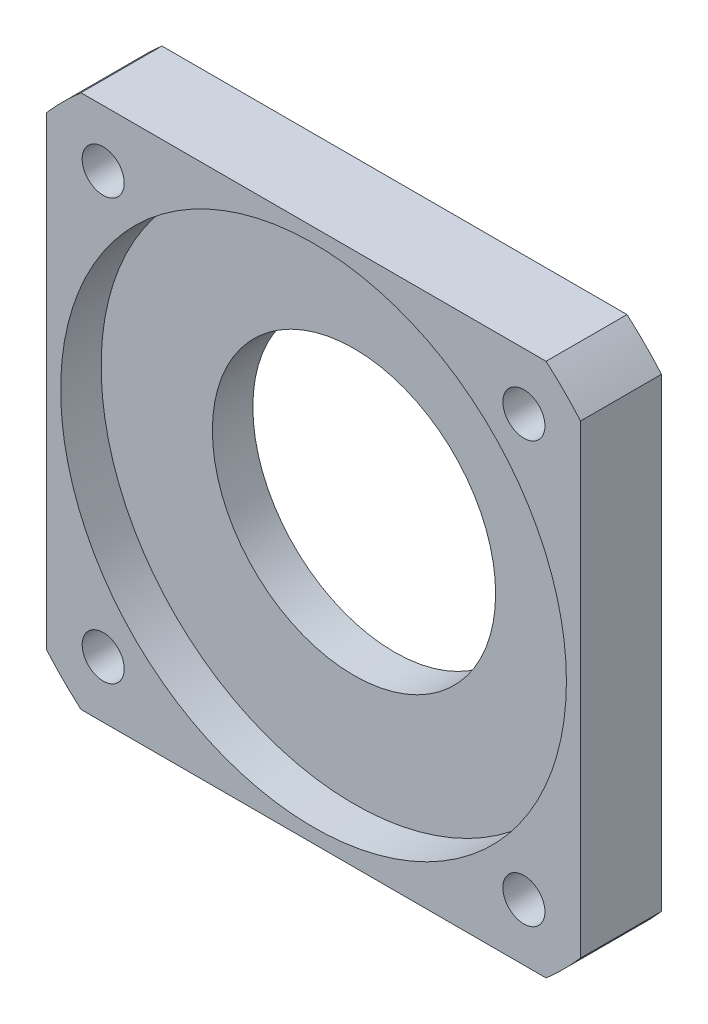
SolidWorks part; units mm, degrees
material "2024-T3"
ref_plane "Front Plane" through (0, 0, 0) normal (0, 0, 1) x (1, 0, 0)
ref_plane "Top Plane" through (0, 0, 0) normal (0, 1, 0) x (1, 0, 0)
ref_plane "Right Plane" through (0, 0, 0) normal (1, 0, 0) x (0, 0, -1)
sketch "Sketch1" plane through (0, 0, 0) normal (0, 0, 1) x (1, 0, 0)
  line L0 (0, 0) -> (41.91, 41.91) construction
  line L1 (0, 0) -> (41.91, 0)
  line L2 (0, 0) -> (0, 41.91)
  line L3 (0, 41.91) -> (41.91, 41.91)
  line L4 (41.91, 0) -> (41.91, 41.91)
  line L5 (4.4493, 37.4607) -> (20.955, 20.955) construction
  circle A0 centre (37.4607, 37.4607) radius 1.6497
  circle A1 centre (37.4607, 4.4493) radius 1.6497
  circle A2 centre (4.4493, 4.4493) radius 1.6497
  circle A3 centre (4.4493, 37.4607) radius 1.6497
  circle A4 centre (20.955, 20.955) radius 11.1125
  point P7 (20.955, 20.955)
  point P17 (20.955, 20.955)
  dimension "D3" = 3.2995
  dimension "D7" = 22.225
  dimension "D1" = 41.91
  dimension "D2" = 41.91
  dimension "D4" = 23.3426
  dimension "D6" = 23.3426
  dimension "D5" = 4
extrude "Boss-Extrude1" add sketch "Sketch1" along normal blind 6.35
sketch "Sketch2" plane through (0, 0, 6.35) normal (0, 0, 1) x (1, 0, 0)
  circle A0 centre (20.955, 20.955) radius 27.7876
  circle A1 centre (20.955, 20.955) radius 62.5657
  dimension "D1" = 55.5752
extrude "Cut-Extrude1" cut sketch "Sketch2" against normal through all
sketch "Sketch3" plane through (0, 0, 6.35) normal (0, 0, 1) x (1, 0, 0)
  circle A0 centre (20.955, 20.955) radius 19.8438
  dimension "D1" = 39.6875
extrude "Cut-Extrude2" cut sketch "Sketch3" against normal blind 3.175
